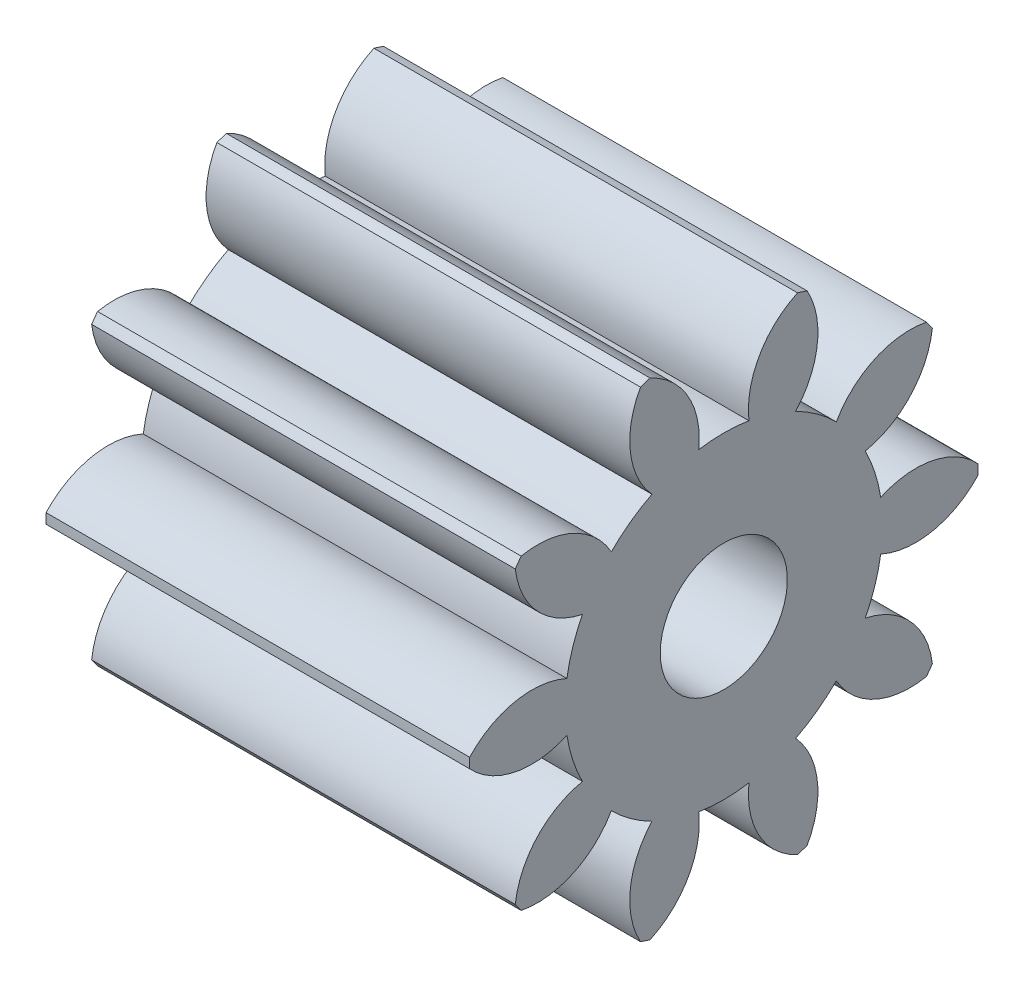
SolidWorks part; units mm, degrees
ref_plane "Plane1" through (0, 0, 0) normal (0, 0, 1) x (1, 0, 0)
ref_plane "Plane2" through (0, 0, 0) normal (0, 1, 0) x (1, 0, 0)
ref_plane "Plane3" through (0, 0, 0) normal (1, 0, 0) x (0, 0, -1)
sketch "HoldingSke" plane through (0, 0, 0) normal (0, 1, 0) x (1, 0, 0)
  line L0 (0, 0) -> (0.9848, -0.1736)
  line L1 (-15, 0) -> (100, 0) construction
  line L2 (0, 0) -> (-2.1039, 2.3779)
  line L3 (0, 0) -> (-11.863, 4.5341)
  line L4 (0, 0) -> (8.5048, 1.4996)
  line L5 (0, 0) -> (-46.8476, -17.4728)
  line L6 (0, 0) -> (-8.2896, -5.593)
  line L7 (-2.1039, 2.3779) -> (8.6586, 51.2059)
  line L8 (-76.2, 54.61) -> (-75.7, 54.61)
  line L9 (-71.009, 38.7566) -> (-53.1078, 45.2721)
  line L10 (-76.2, 71.12) -> (104.1128, 71.12)
  line L11 (0, 0) -> (-10, 0)
  line L12 (-76.2, 101.6) -> (-76.162, 101.6)
  line L13 (24.9733, 27.94) -> (52.9518, 28.4284)
  line L14 (24.9733, 27.94) -> (24.9743, 27.94)
  line L15 (24.9733, 27.94) -> (100.4006, 29.5858)
  line L16 (-63.627, -1) -> (-12.827, -1)
  circle A0 centre (0, 0) radius 1.5
  circle A1 centre (0, 0) radius 3.749
  circle A2 centre (0, 0) radius 37.5
  circle A3 centre (0, 0) radius 1.5
  dimension "MHD" = 7.498
  dimension "Hub_dia" = 75
  dimension "Bore" = 3
  dimension "MBD" = 3
  dimension "Num_teeth" = 10
  dimension "Pitch" = 1
  dimension "Overall_len" = 50
  dimension "Show_teeth" = 10
  dimension "Thickness" = 10
  dimension "OAL" = 50.0001
  dimension "T_dim" = 0.5
  dimension "Ap" = 20
  dimension "H" = 19.05
  dimension "Pitch_radius" = 180.3128
  dimension "Width" = 10
  dimension "Backlash" = 0.038
  dimension "Addendum_fac" = 1
  dimension "Dedendum_fac" = 1.25
  dimension "Clearance_fac" = 0.25
  dimension "Dedendum_add" = 0.001
  dimension "Module" = 1
sketch "BasProSke" plane through (0, 0, 0) normal (0, 1, 0) x (1, 0, 0)
  line L0 (-10, 0) -> (60, 0) construction
  line L1 (0, 0) -> (0, 6)
  line L2 (0, 0) -> (10, 0)
  line L3 (10, 0) -> (10, 6)
  line L4 (10, 6) -> (0, 6)
  dimension "Thickness" = 10
  dimension "Diameter" = 12
revolve "Base-Revolve" add sketch "BasProSke" angle 360 about L0
sketch "TooCutSke" plane through (0, 0, 0) normal (1, 0, 0) x (0, 0, -1)
  line L1 (0, 0) -> (0, 107) construction
  line L2 (0, 0) -> (-0.8485, 4.9275) construction
  line L3 (0, 0) -> (-3.0584, 9.4126) construction
  line L4 (-0.8485, 4.9275) -> (-1.5292, 4.7063) construction
  arc A0 (0.5928, 3.7018) -> (-0.5928, 3.7018) centre (0, 0) ccw
  arc A1 (1.7758, 5.7578) -> (-1.7758, 5.7578) centre (0, 0) ccw
  circle A2 centre (0, 0) radius 5 construction
  circle A3 centre (0, 0) radius 4.6985 construction
  arc A4 (-0.5928, 3.7018) -> (-1.7758, 5.7578) centre (-2.5801, 3.9267) ccw
  arc A5 (1.7758, 5.7578) -> (0.5928, 3.7018) centre (2.5801, 3.9267) ccw
  dimension "Root_dia" = 7.498
  dimension "Overcut_dia" = 12.0508
  dimension "Pitch_dia" = 10
  dimension "Base_dia" = 9.3969
  dimension "Flank_rad" = 2
  dimension "Half_ang" = 18
  dimension "Half_CT" = 0.7157
extrude "ToothCut" cut sketch "TooCutSke" along normal through all
fillet "Breaks" [suppressed] radius 0.02
fillet "RootFillets" [suppressed] radius 0.251
pattern_circular "TeethCuts" count 10 every 36 about axis through (-10, 0, 0) along (1, 0, 0) of "ToothCut", "RootFillets", "Breaks"
sketch "HubNeaOneSke" plane through (0, 0, 0) normal (-1, 0, 0) x (0, 0, 1)
  circle A0 centre (0, 0) radius 3.749
  dimension "Diameter" = 7.498
extrude "HubNearOne" [suppressed] add sketch "HubNeaOneSke" along normal blind 40.0001
sketch "HubNeaBotSke" plane through (0, 0, 0) normal (-1, 0, 0) x (0, 0, 1)
  circle A0 centre (0, 0) radius 3.749
  dimension "Diameter" = 7.498
extrude "HubNearBoth" [suppressed] add sketch "HubNeaBotSke" along normal blind 20
ref_plane "FarPln" through (10, 0, 0) normal (1, 0, 0) x (0, 0, -1)
sketch "HubFarSke" plane through (10, 0, 0) normal (1, 0, 0) x (0, 0, -1)
  circle A0 centre (0, 0) radius 3.749
  dimension "Diameter" = 7.498
extrude "HubFar" [suppressed] add sketch "HubFarSke" along normal blind 20
sketch "BorSke" plane through (0, 0, 0) normal (1, 0, 0) x (0, 0, -1)
  circle A0 centre (0, 0) radius 1.5
  dimension "Diameter" = 3
extrude "Bore" cut sketch "BorSke" along normal mid plane 100.0001
sketch "KeySke" plane through (0, 0, 0) normal (1, 0, 0) x (0, 0, -1)
  line L0 (-0.6, 0) -> (-0.6, 2)
  line L1 (-0.6, 2) -> (0.6, 2)
  line L2 (0.6, 2) -> (0.6, 0)
  line L3 (0, 0) -> (0, 34) construction
  line L4 (-0.6, 0) -> (0.6, 0)
  dimension "Offset" = 2
  dimension "Width" = 1.2
extrude "Keyway" [suppressed] cut sketch "KeySke" along normal mid plane 100.0001
pattern_circular "Keyway2" [suppressed] count 2 every 90 about axis through (-10, 0, 0) along (1, 0, 0)
equation "' \"Module@HoldingSke\" = 6.35"
equation "' \"Num_teeth@HoldingSke\" = 12"
equation "' \"Ap@HoldingSke\" =  20"
equation "' \"Ap@HoldingSke\" = 20"
equation "' \"Width@HoldingSke\" = 0.5 * 25.4"
equation "' \"Hub_dia@HoldingSke\"= 1 * 25.4"
equation "' \"Hub_dia@HoldingSke\" = 1 * 25.4"
equation "' \"Overall_len@HoldingSke\" = 1.0 * 25.4"
equation "' \"Bore@HoldingSke\" = 0.75 * 25.4"
equation "' \"T_dim@HoldingSke\" = 0.1 * 25.4"
equation "' \"Width@KeySke\" = 0.25 * 25.4"
equation "' \"Show_teeth@HoldingSke\" = 13"
equation "' \"Backlash@HoldingSke\" = 0.009 * 25.4"
equation "' \"Addendum_fac@HoldingSke\" = 1.0"
equation "' \"Dedendum_fac@HoldingSke\" = 1.25"
equation "' \"Dedendum_add@HoldingSke\" = 0.00005 * 25.4"
equation "' \"Clearance_fac@HoldingSke\" = 0.25"
equation "\"Pitch@HoldingSke\" = 1 / \"Module@HoldingSke\""
equation "\"Overcut_dia@TooCutSke\" = (\"Num_teeth@HoldingSke\" + 2 * \"Addendum_fac@HoldingSke\") / \"Pitch@HoldingSke\" + 0.002 * 25.4"
equation "\"Pitch_dia@TooCutSke\" = \"Num_teeth@HoldingSke\" / \"Pitch@HoldingSke\""
equation "\"Base_dia@TooCutSke\" = \"Num_teeth@HoldingSke\" / \"Pitch@HoldingSke\" * cos((\"Ap@HoldingSke\"  * 3.14159265 / 180))"
equation "\"Root_dia@TooCutSke\" = (\"Num_teeth@HoldingSke\" + 2) / \"Pitch@HoldingSke\" - 2 * (\"Addendum_fac@HoldingSke\" + \"Dedendum_fac@HoldingSke\") / \"Pitch@HoldingSke\" - \"Dedendum_add@HoldingSke\" * 2"
equation "\"Half_ang@TooCutSke\" = 180 / \"Num_teeth@HoldingSke\""
equation "\"Half_CT@TooCutSke\" = \"Num_teeth@HoldingSke\" / \"Pitch@HoldingSke\" * sin((3.14159265 / 2 / \"Num_teeth@HoldingSke\")) / 2 - 7 * \"Backlash@HoldingSke\" / 4"
equation "\"Flank_rad@TooCutSke\" = \"Num_teeth@HoldingSke\" / \"Pitch@HoldingSke\" / 5"
equation "\"Radius@RootFillets\" = \"Clearance_fac@HoldingSke\" / \"Pitch@HoldingSke\" + \"Dedendum_add@HoldingSke\""
equation "\"Break_rad@Breaks\" = 0.02 / \"Pitch@HoldingSke\""
equation "\"Thickness@HoldingSke\" = \"Width@HoldingSke\""
equation "\"OAL@HoldingSke\" = \"Thickness@HoldingSke\""
equation "\"MHD@HoldingSke\" = (\"Num_teeth@HoldingSke\" + 2) / \"Pitch@HoldingSke\" - 2 * (\"Addendum_fac@HoldingSke\" + \"Dedendum_fac@HoldingSke\")  / \"Pitch@HoldingSke\" - \"Dedendum_add@HoldingSke\" * 2"
equation "\"MBD@HoldingSke\" = (\"Num_teeth@HoldingSke\" + 2) / \"Pitch@HoldingSke\" - 2 * (\"Addendum_fac@HoldingSke\" + \"Dedendum_fac@HoldingSke\")  / \"Pitch@HoldingSke\" - \"Dedendum_add@HoldingSke\" * 2 - 0.002 * 25.4"
equation "\"MHD@HoldingSke\" = ((sgn( \"MHD@HoldingSke\" - \"Hub_dia@HoldingSke\" )-1)*( \"MHD@HoldingSke\" - \"Hub_dia@HoldingSke\" ))/-2+ \"Hub_dia@HoldingSke\""
equation "\"MBD@HoldingSke\" = ((sgn( \"MBD@HoldingSke\" - \"Bore@HoldingSke\" )-1)*( \"MBD@HoldingSke\" - \"Bore@HoldingSke\" ))/-2+ \"Bore@HoldingSke\""
equation "\"OAL@HoldingSke\" = ((sgn( \"OAL@HoldingSke\" - \"Overall_len@HoldingSke\" )+1)*( \"OAL@HoldingSke\" - \"Overall_len@HoldingSke\" ))/2 + \"Overall_len@HoldingSke\" + 0.000002 * 25.4"
equation "\"Num_teeth@TeethCuts\" = int( \"Show_teeth@HoldingSke\" ) + 1"
equation "\"Num_teeth@TeethCuts\" = ((sgn( \"Num_teeth@TeethCuts\" - \"Num_teeth@HoldingSke\" )-1)*( \"Num_teeth@TeethCuts\" - \"Num_teeth@HoldingSke\" ))/-2+ \"Num_teeth@HoldingSke\""
equation "\"Num_teeth@TeethCuts\" = ((sgn( \"Num_teeth@TeethCuts\" - 2.0)+1)*( \"Num_teeth@TeethCuts\" - 2.0))/2 +2.0"
equation "\"Angle@TeethCuts\" = 360.0 / \"Num_teeth@HoldingSke\""
equation "\"Diameter@BasProSke\" = (\"Num_teeth@HoldingSke\" + 2 * \"Addendum_fac@HoldingSke\") / \"Pitch@HoldingSke\""
equation "\"Thickness@BasProSke\"  = \"Thickness@HoldingSke\""
equation "' \"Fillet_rad@BasProSke\" =  \"Thickness@HoldingSke\" * 0.05"
equation "' \"Fillet_rad@BasProSke\" = \"Thickness@HoldingSke\" * 0.05"
equation "\"MHD@HoldingSke\" = ((sgn( \"MHD@HoldingSke\" - \"Root_dia@TooCutSke\" )-1)*( \"MHD@HoldingSke\" - \"Root_dia@TooCutSke\" ))/-2+ \"Root_dia@TooCutSke\""
equation "\"Diameter@HubNeaOneSke\" = \"MHD@HoldingSke\""
equation "\"Length@HubNearOne\" = \"OAL@HoldingSke\" - \"Thickness@BasProSke\""
equation "\"Diameter@HubNeaBotSke\" = \"MHD@HoldingSke\""
equation "\"Length@HubNearBoth\" = ( \"OAL@HoldingSke\" - \"Thickness@BasProSke\" ) / 2.0"
equation "\"Thickness@FarPln\" = \"Thickness@BasProSke\""
equation "\"Diameter@HubFarSke\" = \"MHD@HoldingSke\""
equation "\"Length@HubFar\" = ( \"OAL@HoldingSke\" - \"Thickness@BasProSke\" ) / 2.0"
equation "\"Diameter@BorSke\" = \"MBD@HoldingSke\""
equation "\"D1@Bore\" = \"OAL@HoldingSke\" * 2.0"
equation "\"D1@Keyway\" = \"OAL@HoldingSke\" * 2.0"
equation "\"Offset@KeySke\" = \"T_dim@HoldingSke\" + \"MBD@HoldingSke\" / 2.0"
